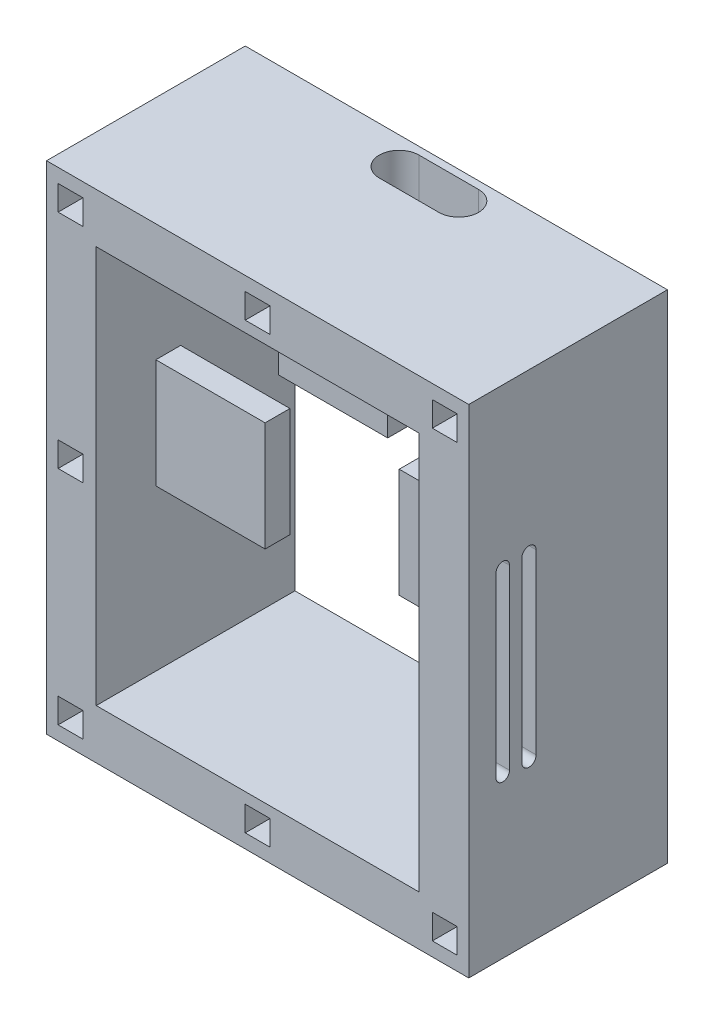
SolidWorks part; units mm, degrees
ref_plane "Front Plane" through (0, 0, 0) normal (1, 0, 0) x (0, 1, 0)
ref_plane "Top Plane" through (0, 0, 0) normal (0, 0, 1) x (0, 1, 0)
ref_plane "Right Plane" through (0, 0, 0) normal (0, 1, 0) x (-1, 0, 0)
sketch "Sketch1" plane through (0, 0, 0) normal (0, 0, 1) x (0, 1, 0)
  line L1 (-40, 32.5) -> (40, 32.5)
  line L2 (-40, 32.5) -> (-40, -32.5)
  line L3 (-40, -32.5) -> (40, -32.5)
  line L4 (40, 32.5) -> (40, -32.5)
  line L5 (-40, 32.5) -> (40, -32.5) construction
  line L6 (-40, -32.5) -> (40, 32.5) construction
  line L7 (-50, 42.5) -> (50, 42.5)
  line L8 (-50, 42.5) -> (-50, -42.5)
  line L9 (-50, -42.5) -> (50, -42.5)
  line L10 (50, 42.5) -> (50, -42.5)
  line L11 (-50, 42.5) -> (50, -42.5) construction
  line L12 (-50, -42.5) -> (50, 42.5) construction
  point P0 (0, 0)
  point P6 (0, 0)
  dimension "D1" = 80
  dimension "D2" = 65
  dimension "D3" = 10
  dimension "D4" = 10
extrude "Boss-Extrude1" add sketch "Sketch1" along normal blind 40
ref_plane "Plane8" through (0, 0, 16) normal (0, 0, 1) x (1, 0, 0)
sketch "Sketch5" plane through (0, 0, 0) normal (0, 0, -1) x (1, 0, 0)
  line L0 (-42.5, 50) -> (42.5, 50)
  line L1 (42.5, 50) -> (42.5, -50)
  line L2 (42.5, -50) -> (-42.5, -50)
  line L3 (-42.5, -50) -> (-42.5, 50) construction
  line L4 (42.5, -50) -> (-42.5, -50) construction
  line L5 (-42.5, -50) -> (-42.5, 50)
sketch "Sketch12" plane through (42.5, 0, 0) normal (1, 0, 0) x (0, 1, 0)
  line L0 (0, 0) -> (0, 40) construction
  line L1 (-50, 40) -> (50, 40) construction
  line L2 (-17.8704, 33.1583) -> (17.8704, 33.1583) construction
  line L3 (-17.8704, 34.5176) -> (17.8704, 34.5176)
  line L4 (-17.8704, 31.7989) -> (17.8704, 31.7989)
  line L5 (-17.8704, 27.8742) -> (17.8704, 27.8742) construction
  line L6 (-17.8704, 29.3165) -> (17.8704, 29.3165)
  line L7 (-17.8704, 26.432) -> (17.8704, 26.432)
  arc A0 (-17.8704, 34.5176) -> (-17.8704, 31.7989) centre (-17.8704, 33.1583) ccw
  arc A1 (17.8704, 31.7989) -> (17.8704, 34.5176) centre (17.8704, 33.1583) ccw
  arc A2 (-17.8704, 29.3165) -> (-17.8704, 26.432) centre (-17.8704, 27.8742) ccw
  arc A3 (17.8704, 26.432) -> (17.8704, 29.3165) centre (17.8704, 27.8742) ccw
  point P7 (0, 33.1583)
  point P14 (0, 27.8742)
  point P19 (0, 20.8123)
  point P20 (0, 15.6775)
  point P21 (0, 0)
  point P22 (0, 20.6383)
  point P23 (0, 15.3294)
  point P24 (0, 24.9557)
  point P25 (0, 19.8206)
  point P26 (0, 33.1583)
  point P27 (0, 27.8742)
sketch "Sketch14" plane through (0, 0, 40) normal (0, 0, 1) x (1, 0, 0)
  line L0 (0, 0) -> (0, 50) construction
  line L1 (-40.1711, 47.1965) -> (-35.1711, 47.1965)
  line L2 (-40.1711, 47.1965) -> (-40.1711, 42.1965)
  line L3 (-40.1711, 42.1965) -> (-35.1711, 42.1965)
  line L4 (-35.1711, 47.1965) -> (-35.1711, 42.1965)
  line L5 (-40.1711, 47.1965) -> (-35.1711, 42.1965) construction
  line L6 (-40.1711, 42.1965) -> (-35.1711, 47.1965) construction
  line L7 (42.5, 50) -> (-42.5, 50) construction
  line L8 (-42.5, 0) -> (42.5, 0) construction
  line L9 (-42.5, 50) -> (-42.5, -50) construction
  line L10 (42.5, -50) -> (42.5, 50) construction
  line L11 (-40.1711, -42.1965) -> (-35.1711, -47.1965) construction
  line L12 (-40.1711, -47.1965) -> (-35.1711, -42.1965) construction
  line L13 (-35.1711, -47.1965) -> (-35.1711, -42.1965)
  line L14 (-40.1711, -42.1965) -> (-35.1711, -42.1965)
  line L15 (-40.1711, -47.1965) -> (-40.1711, -42.1965)
  line L16 (-40.1711, -47.1965) -> (-35.1711, -47.1965)
  line L17 (40.1711, 42.1965) -> (35.1711, 47.1965) construction
  line L18 (40.1711, 47.1965) -> (35.1711, 42.1965) construction
  line L19 (35.1711, 47.1965) -> (35.1711, 42.1965)
  line L20 (40.1711, 42.1965) -> (35.1711, 42.1965)
  line L21 (40.1711, 47.1965) -> (40.1711, 42.1965)
  line L22 (40.1711, 47.1965) -> (35.1711, 47.1965)
  line L23 (40.1711, -47.1965) -> (35.1711, -42.1965) construction
  line L24 (40.1711, -42.1965) -> (35.1711, -47.1965) construction
  line L25 (40.1711, -47.1965) -> (35.1711, -47.1965)
  line L26 (40.1711, -47.1965) -> (40.1711, -42.1965)
  line L27 (40.1711, -42.1965) -> (35.1711, -42.1965)
  line L28 (35.1711, -47.1965) -> (35.1711, -42.1965)
  line L29 (-2.5, 47.1965) -> (2.5, 47.1965)
  line L30 (-2.5, 47.1965) -> (-2.5, 42.1965)
  line L31 (-2.5, 42.1965) -> (2.5, 42.1965)
  line L32 (2.5, 47.1965) -> (2.5, 42.1965)
  line L33 (-2.5, 47.1965) -> (2.5, 42.1965) construction
  line L34 (-2.5, 42.1965) -> (2.5, 47.1965) construction
  line L35 (-2.5, -42.1965) -> (2.5, -47.1965) construction
  line L36 (-2.5, -47.1965) -> (2.5, -42.1965) construction
  line L37 (2.5, -47.1965) -> (2.5, -42.1965)
  line L38 (-2.5, -42.1965) -> (2.5, -42.1965)
  line L39 (-2.5, -47.1965) -> (-2.5, -42.1965)
  line L40 (-2.5, -47.1965) -> (2.5, -47.1965)
  line L41 (-40.1711, 2.5) -> (-35.1711, 2.5)
  line L42 (-40.1711, 2.5) -> (-40.1711, -2.5)
  line L43 (-40.1711, -2.5) -> (-35.1711, -2.5)
  line L44 (-35.1711, 2.5) -> (-35.1711, -2.5)
  line L45 (-40.1711, 2.5) -> (-35.1711, -2.5) construction
  line L46 (-40.1711, -2.5) -> (-35.1711, 2.5) construction
  point P0 (-37.6711, 44.6965)
  point P20 (-37.6711, -44.6965)
  point P25 (37.6711, 44.6965)
  point P30 (37.6711, -44.6965)
  point P31 (0, 44.6965)
  point P40 (0, -44.6965)
  point P41 (-37.6711, 0)
  point P46 (-34.0406, 41.696)
  point P47 (-34.0252, 41.2905)
  point P48 (0, 0)
  point P49 (-35.8451, 43.3381)
  point P50 (-37.3852, 43.9139)
  point P51 (-35.4355, 42.9593)
  point P52 (-37.6711, 44.6965)
  dimension "D1" = 5
  dimension "D2" = 5
  dimension "D3" = 5
  dimension "D4" = 5
  dimension "D5" = 5
  dimension "D6" = 5
extrude "Cut-Extrude11" cut sketch "Sketch14" against normal blind 10
sketch "Sketch22" plane through (0, 50, 0) normal (0, 1, 0) x (-1, 0, 0)
  line L0 (-6, 5.5212) -> (6, 5.5212) construction
  line L1 (-6, 9.5212) -> (6, 9.5212)
  line L2 (-6, 1.5212) -> (6, 1.5212)
  arc A0 (-6, 9.5212) -> (-6, 1.5212) centre (-6, 5.5212) ccw
  arc A1 (6, 1.5212) -> (6, 9.5212) centre (6, 5.5212) ccw
  point P2 (0, 5.5212)
  point P7 (0, 8.649)
  point P8 (0, 7.6837)
  point P9 (0, 6.5146)
  point P10 (0, 5.5212)
  dimension "D1" = 8
  dimension "D2" = 12
extrude "Cut-Extrude16" cut sketch "Sketch22" against normal up to next
sketch "Sketch24" plane through (0, 0, 16) normal (0, 0, 1) x (1, 0, 0)
  line L0 (32.5, 13.7165) -> (10.5, 13.7165)
  line L1 (32.5, -40) -> (32.5, 40) construction
  line L2 (10.5, 13.7165) -> (10.5, -8.2835)
  line L3 (10.5, -8.2835) -> (32.5, -8.2835)
  line L8 (-32.5, 40) -> (-32.5, -40)
  line L9 (32.5, 40) -> (-32.5, 40)
  line L10 (32.5, -40) -> (32.5, 40)
  line L11 (-32.5, -40) -> (32.5, -40)
  line L14 (32.5, -8.2835) -> (32.5, 13.7165)
  dimension "D1" = 22
  dimension "D2" = 22
  dimension "D3" = 0
extrude "Boss-Extrude13" add sketch "Sketch24" along normal blind 6
extrude "Cut-Extrude17" cut sketch "Sketch12" against normal up to next
sketch "Sketch32" plane through (0, 0, 16) normal (0, 0, 1) x (1, 0, 0)
  line L0 (-13.8104, 40) -> (-13.8104, 18)
  line L1 (32.5, 40) -> (-32.5, 40) construction
  line L2 (-13.8104, 18) -> (8.1896, 18)
  line L3 (8.1896, 18) -> (8.1896, 40)
  line L8 (-32.5, 40) -> (-32.5, -40)
  line L9 (32.5, 40) -> (-32.5, 40)
  line L10 (32.5, -40) -> (32.5, 40)
  line L11 (-32.5, -40) -> (32.5, -40)
  line L13 (8.1896, 40) -> (-13.8104, 40)
  dimension "D1" = 22
  dimension "D2" = 22
  dimension "D3" = 0
extrude "Boss-Extrude17" add sketch "Sketch32" along normal blind 6
sketch "Sketch33" plane through (0, 0, 0) normal (0, 0, -1) x (1, 0, 0)
  line L0 (-37.6711, 42.1965) -> (-37.6711, 47.1965) construction
  line L1 (-35.1711, 42.1965) -> (-40.1711, 42.1965) construction
  line L2 (-40.1711, 47.1965) -> (-35.1711, 47.1965) construction
  line L3 (0, 42.1965) -> (0, 47.1965) construction
  line L4 (-40.1711, 47.1965) -> (-35.1711, 47.1965)
  line L5 (-40.1711, 47.1965) -> (-40.1711, 42.1965)
  line L6 (-40.1711, 42.1965) -> (-35.1711, 42.1965)
  line L7 (-35.1711, 47.1965) -> (-35.1711, 42.1965)
  line L8 (-40.1711, 47.1965) -> (-35.1711, 42.1965) construction
  line L9 (-40.1711, 42.1965) -> (-35.1711, 47.1965) construction
  line L10 (2.5, 42.1965) -> (-2.5, 42.1965) construction
  line L11 (-2.5, 47.1965) -> (2.5, 47.1965) construction
  line L12 (37.6711, 42.1965) -> (37.6711, 47.1965) construction
  line L13 (-2.5, 47.1965) -> (2.5, 47.1965)
  line L14 (-2.5, 47.1965) -> (-2.5, 42.1965)
  line L15 (-2.5, 42.1965) -> (2.5, 42.1965)
  line L16 (2.5, 47.1965) -> (2.5, 42.1965)
  line L17 (-2.5, 47.1965) -> (2.5, 42.1965) construction
  line L18 (-2.5, 42.1965) -> (2.5, 47.1965) construction
  line L19 (40.1711, 42.1965) -> (35.1711, 42.1965) construction
  line L20 (35.1711, 47.1965) -> (40.1711, 47.1965) construction
  line L21 (-37.6711, -2.5) -> (-37.6711, 2.5) construction
  line L22 (35.1711, 47.1965) -> (40.1711, 47.1965)
  line L23 (35.1711, 47.1965) -> (35.1711, 42.1965)
  line L24 (35.1711, 42.1965) -> (40.1711, 42.1965)
  line L25 (40.1711, 47.1965) -> (40.1711, 42.1965)
  line L26 (35.1711, 47.1965) -> (40.1711, 42.1965) construction
  line L27 (35.1711, 42.1965) -> (40.1711, 47.1965) construction
  line L30 (-35.1711, -2.5) -> (-40.1711, -2.5) construction
  line L31 (-40.1711, 2.5) -> (-35.1711, 2.5) construction
  line L32 (-37.6711, -47.1965) -> (-37.6711, -42.1965) construction
  line L33 (-40.1711, 2.5) -> (-35.1711, 2.5)
  line L34 (-40.1711, 2.5) -> (-40.1711, -2.5)
  line L35 (-40.1711, -2.5) -> (-35.1711, -2.5)
  line L36 (-35.1711, 2.5) -> (-35.1711, -2.5)
  line L37 (-40.1711, 2.5) -> (-35.1711, -2.5) construction
  line L38 (-40.1711, -2.5) -> (-35.1711, 2.5) construction
  line L39 (-35.1711, -47.1965) -> (-40.1711, -47.1965) construction
  line L40 (-40.1711, -42.1965) -> (-35.1711, -42.1965) construction
  line L41 (37.6711, -47.1965) -> (37.6711, -42.1965) construction
  line L42 (-40.1711, -42.1965) -> (-35.1711, -42.1965)
  line L43 (-40.1711, -42.1965) -> (-40.1711, -47.1965)
  line L44 (-40.1711, -47.1965) -> (-35.1711, -47.1965)
  line L45 (-35.1711, -42.1965) -> (-35.1711, -47.1965)
  line L46 (-40.1711, -42.1965) -> (-35.1711, -47.1965) construction
  line L47 (-40.1711, -47.1965) -> (-35.1711, -42.1965) construction
  line L48 (40.1711, -47.1965) -> (35.1711, -47.1965) construction
  line L49 (35.1711, -42.1965) -> (40.1711, -42.1965) construction
  line L50 (40.1711, -42.1965) -> (40.1711, -47.1965) construction
  line L51 (35.1711, -42.1965) -> (40.1711, -42.1965)
  line L52 (35.1711, -42.1965) -> (35.1711, -47.1965)
  line L53 (35.1711, -47.1965) -> (40.1711, -47.1965)
  line L54 (40.1711, -42.1965) -> (40.1711, -47.1965)
  line L55 (35.1711, -42.1965) -> (40.1711, -47.1965) construction
  line L56 (35.1711, -47.1965) -> (40.1711, -42.1965) construction
  point P6 (-37.6711, 44.6965)
  point P18 (0, 44.6965)
  point P30 (37.6711, 44.6965)
  point P42 (-37.6711, 0)
  point P54 (-37.6711, -44.6965)
  point P66 (37.6711, -44.6965)
extrude "Cut-Extrude18" cut sketch "Sketch33" against normal blind 10
ref_plane "Plane11" through (0, 0, 23) normal (0, 0, 1) x (1, 0, 0)
sketch "Sketch36" plane through (0, 0, 23) normal (0, 0, 1) x (1, 0, 0)
  line L0 (-32.5, 14.2964) -> (-10.5, 14.2964)
  line L1 (-32.5, 40) -> (-32.5, -40) construction
  line L2 (-10.5, 14.2964) -> (-10.5, -7.7036)
  line L3 (-10.5, -7.7036) -> (-32.5, -7.7036)
  line L4 (-32.5, -7.7036) -> (-32.5, -40)
  line L5 (-32.5, 14.2964) -> (-32.5, -7.7036)
  line L8 (-32.5, 40) -> (-32.5, -40)
  line L9 (32.5, 40) -> (-32.5, 40)
  line L10 (32.5, -40) -> (32.5, 40)
  line L11 (-32.5, -40) -> (32.5, -40)
  line L12 (-32.5, 40) -> (-32.5, 14.2964)
  line L13 (32.5, 40) -> (-32.5, 40)
  line L14 (32.5, -40) -> (32.5, 40)
  line L15 (-32.5, -40) -> (32.5, -40)
  dimension "D1" = 22
  dimension "D2" = 22
  dimension "D3" = 0
extrude "Boss-Extrude19" add sketch "Sketch36" along normal blind 5 contours L0 L5 L3 L2
